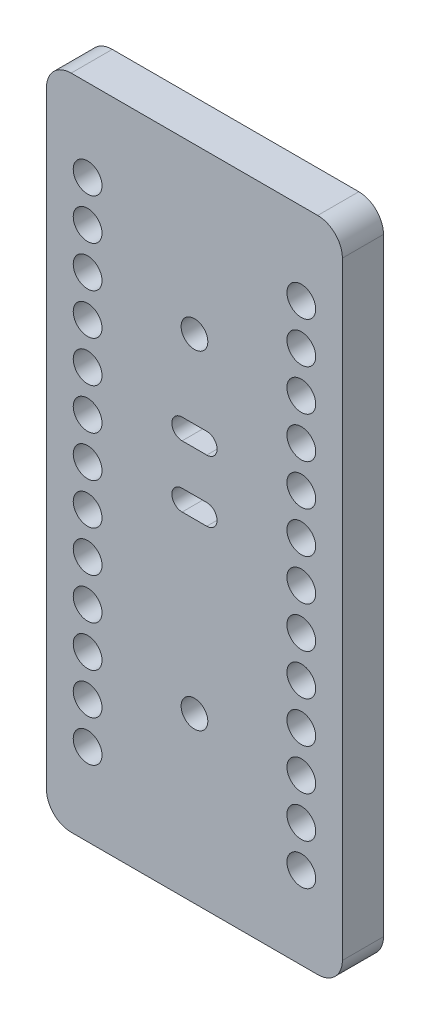
SolidWorks part; units mm, degrees
material "Maple"
ref_plane "Front Plane" through (0, 0, 0) normal (0, 0, 1) x (1, 0, 0)
ref_plane "Top Plane" through (0, 0, 0) normal (0, 1, 0) x (1, 0, 0)
ref_plane "Right Plane" through (0, 0, 0) normal (1, 0, 0) x (0, 0, -1)
sketch "Sketch1" plane through (0, 0, 0) normal (0, 0, 1) x (1, 0, 0)
  line L0 (8, 72) -> (8, 8) construction
  line L1 (0, 0) -> (16, 0)
  line L2 (0, 0) -> (0, 80)
  line L3 (0, 80) -> (16, 80)
  line L4 (16, 0) -> (16, 80)
  line L5 (8, 8) -> (8, 0) construction
  line L6 (6.5, 49.25) -> (9.5, 49.25) construction
  line L7 (6.5, 50.5) -> (9.5, 50.5)
  line L8 (6.5, 48) -> (9.5, 48)
  line L9 (6.5, 41.75) -> (9.5, 41.75) construction
  line L10 (6.5, 43) -> (9.5, 43)
  line L11 (6.5, 40.5) -> (9.5, 40.5)
  line L12 (16, 40) -> (8, 40) construction
  circle A0 centre (8, 72) radius 4 construction
  circle A1 centre (8, 8) radius 4 construction
  arc A2 (6.5, 50.5) -> (6.5, 48) centre (6.5, 49.25) ccw
  arc A3 (9.5, 48) -> (9.5, 50.5) centre (9.5, 49.25) ccw
  arc A4 (6.5, 43) -> (6.5, 40.5) centre (6.5, 41.75) ccw
  arc A5 (9.5, 40.5) -> (9.5, 43) centre (9.5, 41.75) ccw
  circle A6 centre (8, 20) radius 1.625
  circle A7 centre (8, 60) radius 1.625
  point P12 (8, 49.25)
  point P17 (8, 41.75)
  dimension "D2" = 8
  dimension "D10" = 3.25
  dimension "D1" = 8
  dimension "D3" = 64
  dimension "D4" = 8
  dimension "D5" = 8
  dimension "D6" = 8
  dimension "D7" = 3
  dimension "D8" = 2.5
  dimension "D9" = 5
  dimension "D11" = 12
  dimension "D12" = 12
extrude "Boss-Extrude1" add sketch "Sketch1" along normal blind 5
sketch "Sketch2" plane through (0, 0, 5) normal (0, 0, 1) x (1, 0, 0)
  line L0 (16, 80) -> (23, 80)
  line L1 (16, 0) -> (16, 80) construction
  line L2 (26, 77) -> (26, 3)
  line L3 (23, 0) -> (16, 0)
  line L4 (16, 0) -> (16, 80)
  line L5 (16, 80) -> (0, 80) construction
  line L6 (18.936, 80) -> (18.936, 0) construction
  line L7 (21, 70) -> (18.936, 70) construction
  line L8 (-5, 70) -> (-2.936, 70) construction
  line L9 (8, 80) -> (8, 68.1965) construction
  line L10 (-5, 70) -> (-2.936, 70) construction
  line L11 (-2.936, 80) -> (-2.936, 0) construction
  line L12 (0, 0) -> (0, 80)
  line L13 (-7, 0) -> (0, 0)
  line L14 (-10, 77) -> (-10, 3)
  line L15 (0, 80) -> (-7, 80)
  arc A0 (23, 80) -> (26, 77) centre (23, 77) cw
  arc A1 (26, 3) -> (23, 0) centre (23, 3) cw
  circle A2 centre (21, 70) radius 1.75
  circle A3 centre (21, 65) radius 1.75
  arc A4 (-10, 3) -> (-7, 0) centre (-7, 3) ccw
  arc A5 (-7, 80) -> (-10, 77) centre (-7, 77) ccw
  circle A6 centre (21, 60) radius 1.75
  circle A7 centre (21, 55) radius 1.75
  circle A8 centre (21, 50) radius 1.75
  circle A9 centre (21, 45) radius 1.75
  circle A10 centre (21, 40) radius 1.75
  circle A11 centre (21, 35) radius 1.75
  circle A12 centre (21, 30) radius 1.75
  circle A13 centre (21, 25) radius 1.75
  circle A14 centre (21, 20) radius 1.75
  circle A15 centre (21, 15) radius 1.75
  circle A16 centre (21, 10) radius 1.75
  circle A17 centre (-5, 10) radius 1.75
  circle A18 centre (-5, 15) radius 1.75
  circle A19 centre (-5, 20) radius 1.75
  circle A20 centre (-5, 25) radius 1.75
  circle A21 centre (-5, 30) radius 1.75
  circle A22 centre (-5, 35) radius 1.75
  circle A23 centre (-5, 40) radius 1.75
  circle A24 centre (-5, 45) radius 1.75
  circle A25 centre (-5, 50) radius 1.75
  circle A26 centre (-5, 55) radius 1.75
  circle A27 centre (-5, 60) radius 1.75
  circle A28 centre (-5, 65) radius 1.75
  circle A29 centre (-5, 70) radius 1.75
  point P14 (8, 80)
  dimension "D1" = 3.5
  dimension "D4" = 3
  dimension "D7" = 5
  dimension "D2" = 13
  dimension "D3" = 10
  dimension "D5" = 13
  dimension "D6" = 5
extrude "Boss-Extrude2" add sketch "Sketch2" against normal up to surface (5 mm away) up to face at (9.625, 20, 0)
